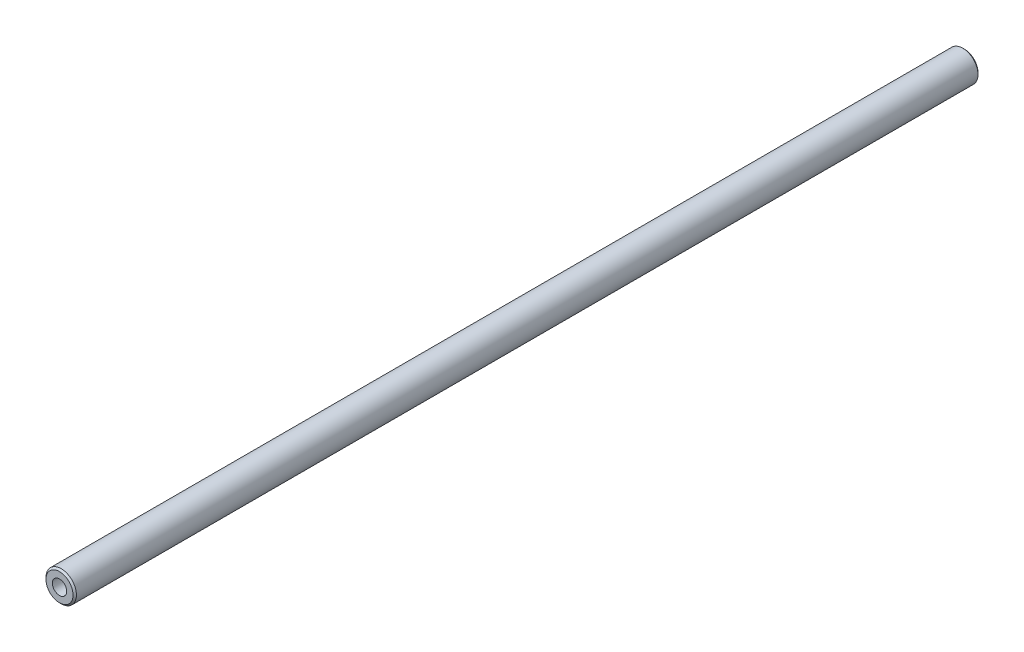
SolidWorks part; units mm, degrees
material "1.4305 (X8CrNiS18-9)"
ref_plane "Ebene1" through (0, 0, 0) normal (0, 0, 1) x (1, 0, 0)
ref_plane "Ebene2" through (0, 0, 0) normal (0, 1, 0) x (1, 0, 0)
ref_plane "Ebene3" through (0, 0, 0) normal (1, 0, 0) x (0, 0, -1)
sketch "Skizze1" plane through (0, 0, 0) normal (0, 0, 1) x (1, 0, 0)
  circle A0 centre (0, 0) radius 9
  dimension "D1" = 18
extrude "Basis-Linear austragen" add sketch "Skizze1" along normal mid plane 535
chamfer "Fase1" distance 1 angle 45 2 edges at (9, 0, -267.5) (9, 0, 267.5)
hole_wizard "Bohrung1" positions "Skizze4" profile "Skizze3" tap size "M10x1.5" standard "Ansi Metrisch"
sketch "Skizze4" plane through (0, 0, 267.5) normal (0, 0, 1) x (1, 0, 0)
  point P0 (0, 0)
sketch "Skizze3" plane through (0, 0, 267.5) normal (1, 0, 0) x (0, -1, 0)
  line L0 (0, 0) -> (0, 25.5537)
  line L1 (0, 25.5537) -> (4.25, 23)
  line L2 (4.25, 23) -> (4.25, 0)
  line L5 (4.25, 0) -> (0, 0)
  line L10 (0, 25.5537) -> (-4.25, 23) construction
  line L11 (0, -6.35) -> (0, 107.95) construction
  dimension "Bohrerdurchmesser" = 8.5
  dimension "Bohrungstiefe" = 23
  dimension "Spitzenwinkel" = 118
cosmetic thread "Gewindedarstellung1" parameters "D1"=20, "D2"=10
